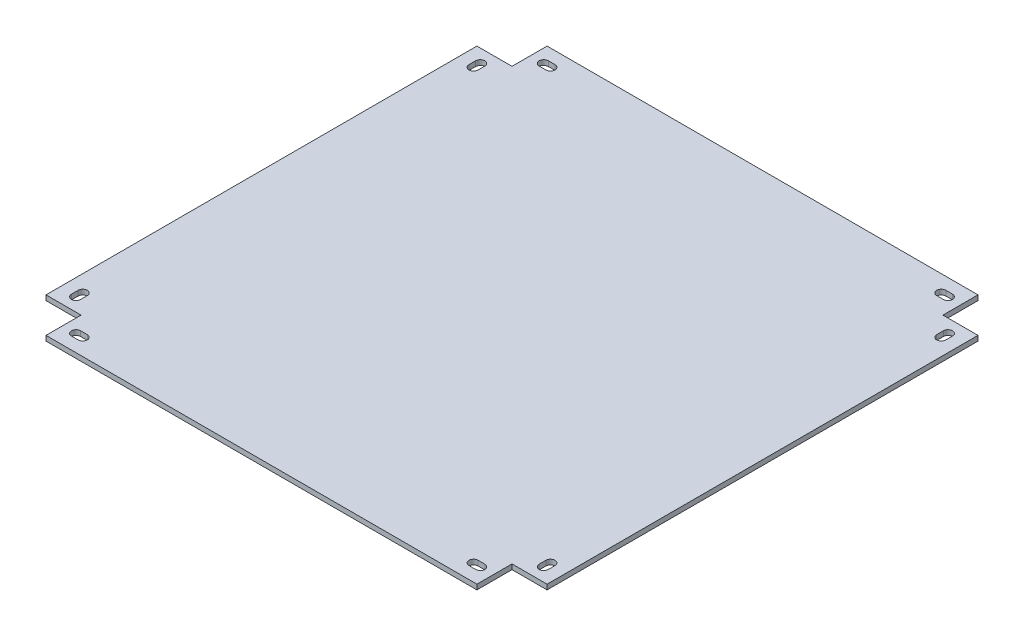
SolidWorks part; units mm, degrees
ref_plane "Front Plane" through (0, 0, 0) normal (0, 0, 1) x (1, 0, 0)
ref_plane "Top Plane" through (0, 0, 0) normal (0, 1, 0) x (1, 0, 0)
ref_plane "Right Plane" through (0, 0, 0) normal (1, 0, 0) x (0, 0, -1)
sketch "Sketch1" plane through (0, 0, 0) normal (0, 1, 0) x (1, 0, 0)
  line L0 (-140, 121) -> (-140, 117) construction
  line L1 (-150, -150) -> (150, -150)
  line L2 (-150, -150) -> (-150, 150)
  line L3 (-150, 150) -> (150, 150)
  line L4 (150, -150) -> (150, 150)
  line L5 (-150, -150) -> (150, 150) construction
  line L6 (-150, 150) -> (150, -150) construction
  line L7 (-150, 150) -> (-129, 150)
  line L8 (-150, 150) -> (-150, 129)
  line L9 (-150, 129) -> (-129, 129)
  line L10 (-129, 150) -> (-129, 129)
  line L11 (-137.25, 121) -> (-137.25, 117)
  line L12 (-142.75, 121) -> (-142.75, 117)
  line L13 (-121, 140) -> (-117, 140) construction
  line L14 (-121, 142.75) -> (-117, 142.75)
  line L15 (-121, 137.25) -> (-117, 137.25)
  line L16 (0, 150) -> (0, 0) construction
  line L17 (0, 0) -> (-150, 0) construction
  line L18 (121, 140) -> (117, 140) construction
  line L19 (121, 142.75) -> (117, 142.75)
  line L20 (121, 137.25) -> (117, 137.25)
  line L21 (140, 121) -> (140, 117) construction
  line L22 (137.25, 121) -> (137.25, 117)
  line L23 (142.75, 121) -> (142.75, 117)
  line L24 (150, 129) -> (129, 129)
  line L25 (129, 150) -> (129, 129)
  line L26 (150, 150) -> (129, 150)
  line L27 (150, 150) -> (150, 129)
  line L28 (-140, -121) -> (-140, -117) construction
  line L29 (-137.25, -121) -> (-137.25, -117)
  line L30 (-142.75, -121) -> (-142.75, -117)
  line L31 (-121, -140) -> (-117, -140) construction
  line L32 (-121, -142.75) -> (-117, -142.75)
  line L33 (-121, -137.25) -> (-117, -137.25)
  line L34 (121, -140) -> (117, -140) construction
  line L35 (121, -142.75) -> (117, -142.75)
  line L36 (121, -137.25) -> (117, -137.25)
  line L37 (140, -121) -> (140, -117) construction
  line L38 (137.25, -121) -> (137.25, -117)
  line L39 (142.75, -121) -> (142.75, -117)
  line L40 (150, -150) -> (129, -150)
  line L41 (129, -150) -> (129, -129)
  line L42 (150, -129) -> (129, -129)
  line L43 (150, -150) -> (150, -129)
  line L44 (-150, -129) -> (-129, -129)
  line L45 (-129, -150) -> (-129, -129)
  line L46 (-150, -150) -> (-129, -150)
  line L47 (-150, -150) -> (-150, -129)
  arc A0 (-137.25, 121) -> (-142.75, 121) centre (-140, 121) ccw
  arc A1 (-142.75, 117) -> (-137.25, 117) centre (-140, 117) ccw
  arc A2 (-121, 142.75) -> (-121, 137.25) centre (-121, 140) ccw
  arc A3 (-117, 137.25) -> (-117, 142.75) centre (-117, 140) ccw
  arc A4 (121, 142.75) -> (121, 137.25) centre (121, 140) cw
  arc A5 (117, 137.25) -> (117, 142.75) centre (117, 140) cw
  arc A6 (137.25, 121) -> (142.75, 121) centre (140, 121) cw
  arc A7 (142.75, 117) -> (137.25, 117) centre (140, 117) cw
  arc A8 (-137.25, -121) -> (-142.75, -121) centre (-140, -121) cw
  arc A9 (-142.75, -117) -> (-137.25, -117) centre (-140, -117) cw
  arc A10 (-121, -142.75) -> (-121, -137.25) centre (-121, -140) cw
  arc A11 (-117, -137.25) -> (-117, -142.75) centre (-117, -140) cw
  arc A12 (121, -142.75) -> (121, -137.25) centre (121, -140) ccw
  arc A13 (117, -137.25) -> (117, -142.75) centre (117, -140) ccw
  arc A14 (137.25, -121) -> (142.75, -121) centre (140, -121) ccw
  arc A15 (142.75, -117) -> (137.25, -117) centre (140, -117) ccw
  point P0 (0, 0)
  point P11 (-140, 119)
  point P16 (-119, 140)
  point P28 (119, 140)
  point P35 (140, 119)
  point P45 (-140, -119)
  point P52 (-119, -140)
  point P59 (119, -140)
  point P66 (140, -119)
  dimension "D5" = 2.75
  dimension "D1" = 300
  dimension "D2" = 300
  dimension "D3" = 21
  dimension "D4" = 4
  dimension "D6" = 10
  dimension "D7" = 10
  dimension "D8" = 10
  dimension "D9" = 10
extrude "Boss-Extrude1" add sketch "Sketch1" along normal blind 3 contours L45 L1 L41 L42 L4 L24 L25 L3 L10 L9 L2 L44 A15 L39 A14 L38 A13 L36 A12 L35 A3 L15 A2 L14 A1 L12 A0 L11 L20 A5 L19 A4 L23 A7 L22 A6 L30 A9 L29 A8 L33 A11 L32
equation "\"D7@Sketch1\"=\"D6@Sketch1\""
